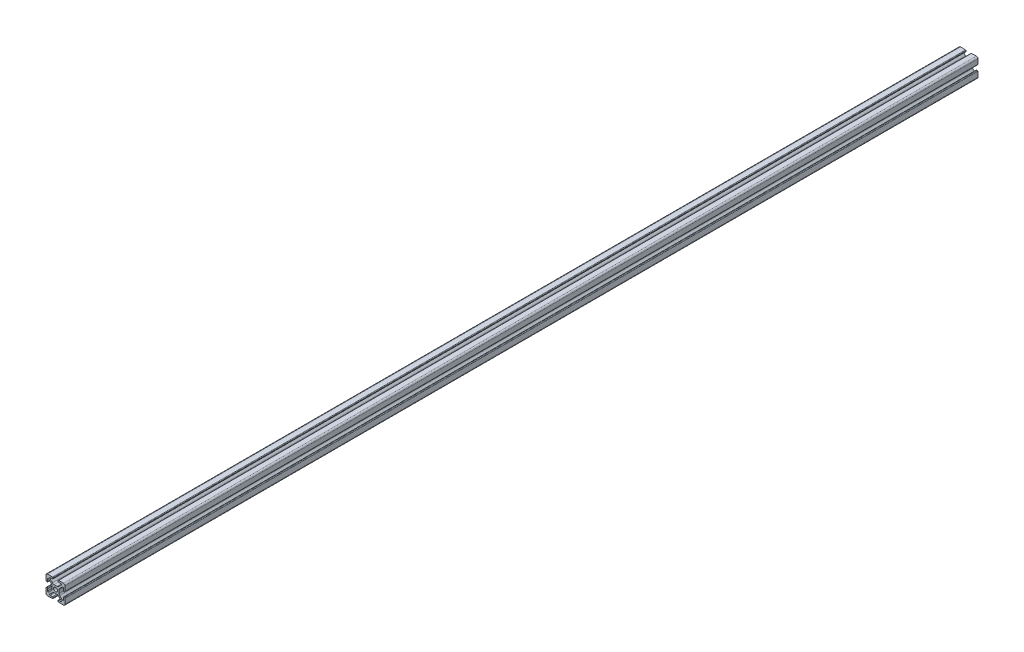
SolidWorks part; units mm, degrees
ref_plane "Front Plane" through (0, 0, 0) normal (0, 0, 1) x (1, 0, 0)
ref_plane "Top Plane" through (0, 0, 0) normal (0, 1, 0) x (1, 0, 0)
ref_plane "Right Plane" through (0, 0, 0) normal (1, 0, 0) x (0, 0, -1)
sketch "Sketch1" plane through (0, 0, 0) normal (0, 0, 1) x (1, 0, 0)
  line L0 (0, 0) -> (0, 12.7) construction
  line L1 (0, 0) -> (12.7, 0) construction
  line L2 (0, 0) -> (-12.7, 12.7) construction
  line L3 (-10.5971, 12.6988) -> (-3.9739, 12.4675)
  line L4 (-12.7, 12.7) -> (0, 12.7) construction
  line L6 (-4.0475, 10.3606) -> (-7.0332, 10.4648)
  line L10 (0, 4.7625) -> (-1.8848, 4.7625)
  line L11 (-4.1299, 5.6924) -> (-7.5996, 9.1622)
  line L24 (0, 0) -> (-12.7, 0) construction
  line L25 (-12.7, 0) -> (0, 0) construction
  line L26 (0, 0) -> (0, -12.7) construction
  line L27 (-12.7, -12.7) -> (-12.7, 12.7) construction
  line L28 (0, 12.7) -> (12.7, 12.7) construction
  line L29 (-3.239, 11.6793) -> (-3.2594, 11.0955)
  line L30 (-12.7, -12.7) -> (12.7, -12.7) construction
  arc A0 (-12.1048, 12.1048) -> (-10.5971, 12.6988) centre (-10.668, 10.668) cw
  arc A6 (-1.8848, 4.7625) -> (-4.1299, 5.6924) centre (-1.8848, 7.9375) cw
  circle A16 centre (0, 0) radius 2.54
  arc A18 (-7.5996, 9.1622) -> (-7.0332, 10.4648) centre (-7.0599, 9.702) cw
  circle A19 centre (-2.3794, 2.3794) radius 0.635 construction
  arc A20 (-4.0475, 10.3606) -> (-3.2594, 11.0955) centre (-4.0209, 11.1221) ccw
  arc A21 (-3.9739, 12.4675) -> (-3.239, 11.6793) centre (-4.0005, 11.7059) cw
  point P15 (0, 0)
  point P42 (-3.1999, 4.7625)
  point P80 (-12.7, 0)
  point P85 (0, -12.7)
  point P88 (0, -12.7)
  dimension "D11" = 2.032
  dimension "D15" = 3.175
  dimension "Center Hole Diameter" = 5.08
  dimension "D6" = 1.27
  dimension "D4" = 0.7633
  dimension "D8" = 0.762
  dimension "D12" = 0.762
  dimension "D1" = 45
  dimension "D2" = 2
  dimension "Rail Width" = 25.4
  dimension "D10" = 2.2098
  dimension "T-Slot Depth" = 7.9375
  dimension "D9" = 2.1082
  dimension "Rail Height" = 25.4
  dimension "D23" = 9.525
  dimension "D5" = 15.6464
  dimension "D3" = 4
  dimension "D7" = 5.7028
  dimension "T-Slot Width" = 6.477
sketch "Sketch2" plane through (0, 0, 0) normal (1, 0, 0) x (0, 0, -1)
  line L0 (-609.6, 0) -> (609.6, 0)
  line L2 (0, 0) -> (0, 12.7) construction
  line L3 (0, 0) -> (0, 12.7) construction
  point P0 (-571.5, 0)
  point P3 (0, 0)
  point P7 (571.5, 0)
  dimension "D1" = 38.1
  dimension "Length" = 1219.2
sketch "Sketch3" plane through (0, 0, 0) normal (0, 0, 1) x (1, 0, 0)
  line L2 (0, 4.7625) -> (-1.8848, 4.7625) construction
  line L5 (-4.1299, 5.6924) -> (-7.5996, 9.1622) construction
  line L6 (-4.0475, 10.3606) -> (-7.0332, 10.4648) construction
  line L7 (-3.239, 11.6793) -> (-3.2594, 11.0955) construction
  line L67 (-10.5971, 12.6988) -> (-3.9739, 12.4675) construction
  line L68 (0, 4.7625) -> (-1.8848, 4.7625)
  line L69 (-4.1299, 5.6924) -> (-7.5996, 9.1622)
  line L70 (-4.0475, 10.3606) -> (-7.0332, 10.4648)
  line L71 (-3.239, 11.6793) -> (-3.2594, 11.0955)
  line L72 (-10.5971, 12.6988) -> (-3.9739, 12.4675)
  line L73 (0, 0) -> (-12.7, 12.7) construction
  line L74 (0, 0) -> (-12.7, 12.7) construction
  line L75 (-12.6988, 10.5971) -> (-12.4675, 3.9739)
  line L76 (-11.6793, 3.239) -> (-11.0955, 3.2594)
  line L77 (-10.3606, 4.0475) -> (-10.4648, 7.0332)
  line L78 (-5.6924, 4.1299) -> (-9.1622, 7.5996)
  line L79 (-4.7625, 0) -> (-4.7625, 1.8848)
  line L80 (-4.7625, 0) -> (-2.54, 0)
  line L82 (0, 4.7625) -> (0, 2.54)
  arc A3 (-4.1299, 5.6924) -> (-1.8848, 4.7625) centre (-1.8848, 7.9375) ccw construction
  circle A10 centre (0, 0) radius 2.54
  arc A56 (0, 2.54) -> (-2.54, 0) centre (0, 0) ccw
  arc A57 (-7.0332, 10.4648) -> (-7.5996, 9.1622) centre (-7.0599, 9.702) ccw construction
  arc A58 (-4.0475, 10.3606) -> (-3.2594, 11.0955) centre (-4.0209, 11.1221) ccw construction
  arc A59 (-3.239, 11.6793) -> (-3.9739, 12.4675) centre (-4.0005, 11.7059) ccw construction
  arc A60 (-10.5971, 12.6988) -> (-12.1048, 12.1048) centre (-10.668, 10.668) ccw construction
  arc A61 (-4.1299, 5.6924) -> (-1.8848, 4.7625) centre (-1.8848, 7.9375) ccw
  arc A62 (-7.0332, 10.4648) -> (-7.5996, 9.1622) centre (-7.0599, 9.702) ccw
  arc A63 (-4.0475, 10.3606) -> (-3.2594, 11.0955) centre (-4.0209, 11.1221) ccw
  arc A64 (-3.239, 11.6793) -> (-3.9739, 12.4675) centre (-4.0005, 11.7059) ccw
  arc A65 (-10.5971, 12.6988) -> (-12.6988, 10.5971) centre (-10.668, 10.668) ccw
  arc A67 (-11.6793, 3.239) -> (-12.4675, 3.9739) centre (-11.7059, 4.0005) cw
  arc A68 (-10.3606, 4.0475) -> (-11.0955, 3.2594) centre (-11.1221, 4.0209) cw
  arc A69 (-10.4648, 7.0332) -> (-9.1622, 7.5996) centre (-9.702, 7.0599) cw
  arc A70 (-5.6924, 4.1299) -> (-4.7625, 1.8848) centre (-7.9375, 1.8848) cw
  dimension "D1" = 0
extrude "Boss-Extrude1" add sketch "Sketch3" along normal mid plane 1219.2
pattern_circular "CirPattern1" count 4 over 360 about axis through (0, 0, 0) along (0, 0, 1) of "Boss-Extrude1"
ref_plane "Contact Plane 1" through (0, 12.7, 0) normal (0, 1, 0) x (1, 0, 0)
ref_plane "Contact Plane 2" through (12.7, 0, 0) normal (1, 0, 0) x (0, 0, -1)
ref_plane "Contact Plane 3" through (0, -12.7, 0) normal (0, -1, 0) x (-1, 0, 0)
ref_plane "Contact Plane 4" through (-12.7, 0, 0) normal (-1, 0, 0) x (0, 0, 1)
equation "\"D1@Sketch2\"=\"Rail Width@Sketch1\"*1.5"
equation "\"D1@Boss-Extrude1\"=\"Length@Sketch2\""
